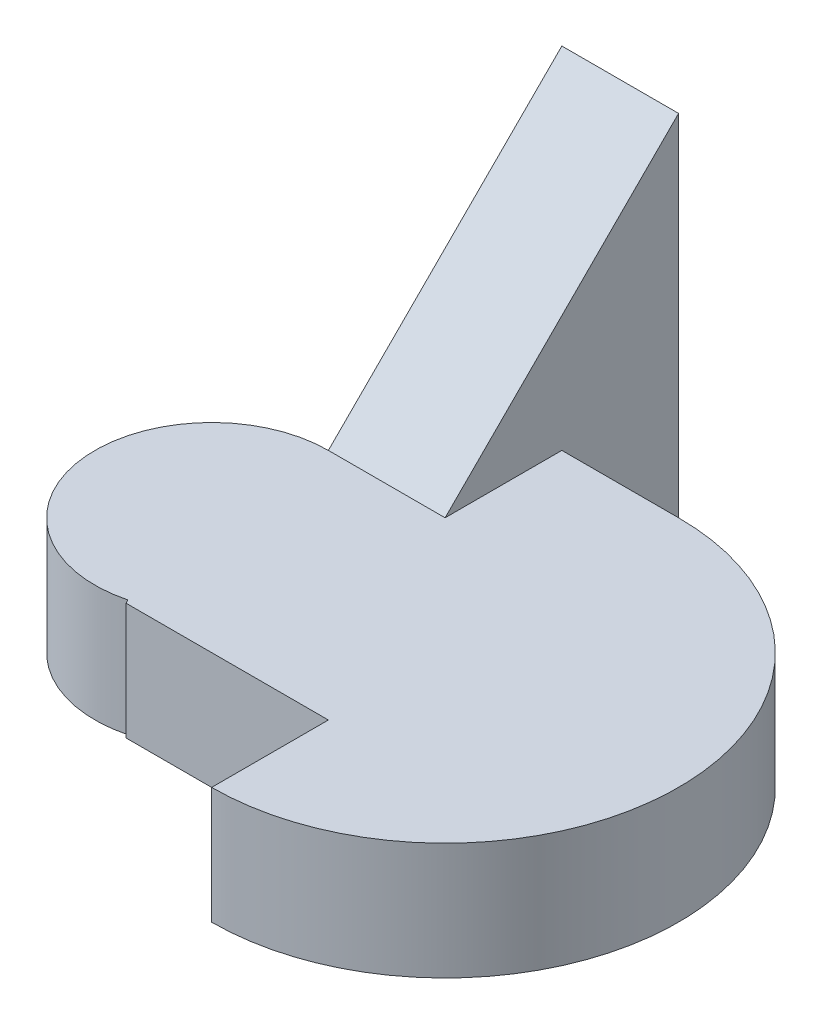
SolidWorks part; units mm, degrees
ref_plane "前基準面" through (0, 0, 0) normal (0, 0, 1) x (1, 0, 0)
ref_plane "上基準面" through (0, 0, 0) normal (0, 1, 0) x (1, 0, 0)
ref_plane "右基準面" through (0, 0, 0) normal (1, 0, 0) x (0, 0, -1)
sketch "草圖1" plane through (0, 0, 0) normal (0, 1, 0) x (1, 0, 0)
  line L0 (0, 0) -> (0, 10)
  line L1 (0, 10) -> (10, 10)
  line L2 (0, 0) -> (-10, 0)
  line L3 (-10, 0) -> (-10, -20)
  line L4 (-10, -20) -> (10, -20)
  line L5 (10, -20) -> (10, -30)
  line L6 (10, 10) -> (10, -20)
  arc A2 (-10, 0) -> (-7.5, -19.6825) centre (-10, -10) ccw
  arc A3 (-7.5, -19.6825) -> (-7.3205, -20) centre (10, -10) ccw
  arc A4 (10, -30) -> (10, 10) centre (10, -10) ccw
  dimension "D1" = 20
  dimension "D2" = 10
  dimension "D3" = 10
  dimension "D4" = 40
  dimension "D5" = 20
  dimension "D6" = 10
extrude "填料-伸長1" add sketch "草圖1" along normal blind 10 contours A2 A3 L4 L6 L1 L0 L2 L3 | L3 A2 | L5 A4 L6
sketch "草圖2" plane through (0, 0, 0) normal (0, -1, 0) x (1, 0, 0)
  line L0 (0, 0) -> (-10, 0)
  line L1 (0, 0) -> (-10, 0) construction
  line L2 (-10, 0) -> (-10, -20)
  line L3 (-10, -20) -> (0, -20)
  line L4 (0, -20) -> (0, 0)
  dimension "D1" = 20
  dimension "D2" = 10
extrude "填料-伸長2" add sketch "草圖2" against normal blind 30
sketch "草圖3" plane through (0, 0, 0) normal (1, 0, 0) x (0, 0, -1)
  line L0 (20, 30) -> (0, 10)
  line L1 (0, 10) -> (0, 30)
  line L2 (0, 30) -> (20, 30)
extrude "除料-伸長1" cut sketch "草圖3" against normal blind 30
